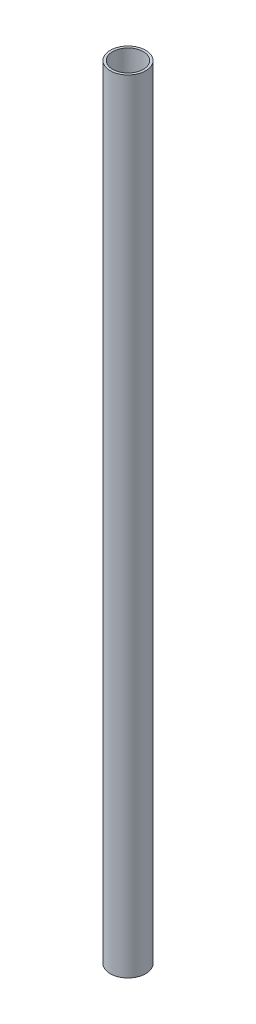
SolidWorks part; units mm, degrees
material "1060 Alloy"
ref_plane "Front Plane" through (0, 0, 0) normal (0, 0, 1) x (1, 0, 0)
ref_plane "Top Plane" through (0, 0, 0) normal (0, 1, 0) x (1, 0, 0)
ref_plane "Right Plane" through (0, 0, 0) normal (1, 0, 0) x (0, 0, -1)
sketch "Sketch1" plane through (0, 0, 0) normal (0, 1, 0) x (1, 0, 0)
  circle A0 centre (0, 0) radius 15
  circle A1 centre (0, 0) radius 13
  dimension "D1" = 2
  dimension "D2" = 30
extrude "Boss-Extrude1" add sketch "Sketch1" along normal blind 661
